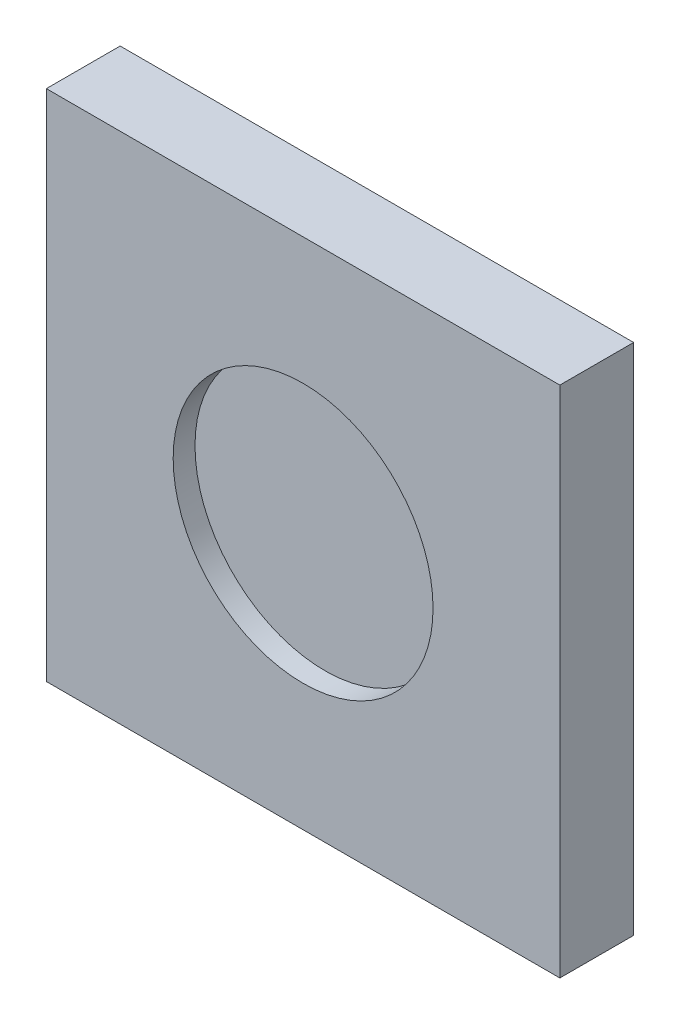
SolidWorks part; units mm, degrees
ref_plane "Front Plane" through (0, 0, 0) normal (0, 0, 1) x (1, 0, 0)
ref_plane "Top Plane" through (0, 0, 0) normal (0, 1, 0) x (1, 0, 0)
ref_plane "Right Plane" through (0, 0, 0) normal (1, 0, 0) x (0, 0, -1)
sketch "Sketch1" plane through (0, 0, 0) normal (0, 0, 1) x (1, 0, 0)
  line L1 (0, 0) -> (49.4, 0)
  line L2 (0, 0) -> (0, 49.4)
  line L3 (0, 49.4) -> (49.4, 49.4)
  line L4 (49.4, 0) -> (49.4, 49.4)
  circle A0 centre (24.7, 24.7) radius 12.5
  dimension "D5" = 25
  dimension "D1" = 49.4
  dimension "D2" = 49.4
  dimension "D3" = 24.7
  dimension "D4" = 24.7
extrude "Boss-Extrude1" add sketch "Sketch1" along normal blind 7.1
sketch "Sketch5" plane through (0, 0, 0) normal (0, 0, -1) x (-1, 0, 0)
  circle A0 centre (-24.7, 24.7) radius 12.5 construction
  circle A1 centre (-24.7, 24.7) radius 12.5
extrude "Boss-Extrude2" add sketch "Sketch5" against normal blind 5
